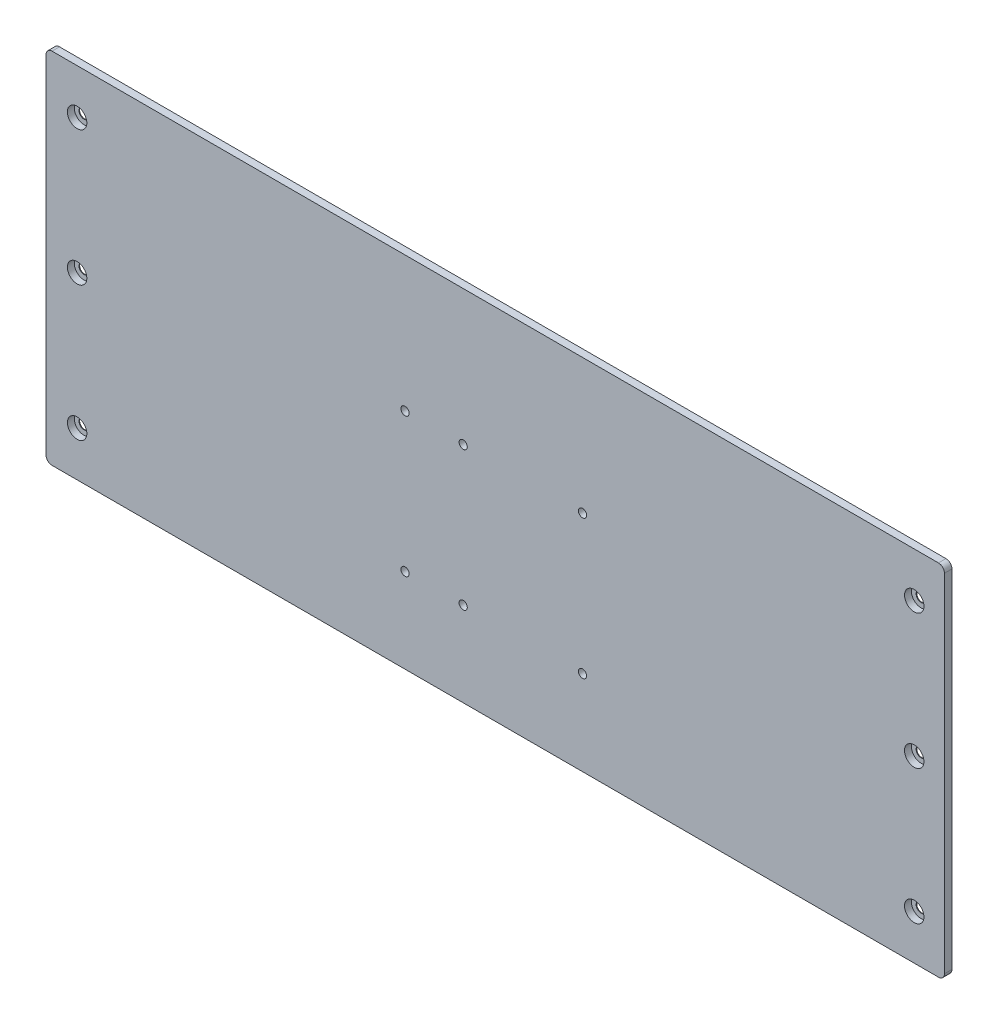
SolidWorks part; units mm, degrees
ref_plane "Front Plane" through (0, 0, 0) normal (0, 0, 1) x (1, 0, 0)
ref_plane "Top Plane" through (0, 0, 0) normal (0, 1, 0) x (1, 0, 0)
ref_plane "Right Plane" through (0, 0, 0) normal (1, 0, 0) x (0, 0, -1)
sketch "Sketch1" plane through (0, 0, 0) normal (0, 0, 1) x (1, 0, 0)
  line L1 (-296.5, -120) -> (296.5, -120)
  line L2 (-300.5, -116) -> (-300.5, 116)
  line L3 (-296.5, 120) -> (296.5, 120)
  line L4 (300.5, -116) -> (300.5, 116)
  line L5 (-300.5, -120) -> (300.5, 120) construction
  line L6 (-300.5, 120) -> (300.5, -120) construction
  arc A0 (-296.5, -120) -> (-300.5, -116) centre (-296.5, -116) cw
  arc A1 (296.5, -120) -> (300.5, -116) centre (296.5, -116) ccw
  arc A2 (300.5, 116) -> (296.5, 120) centre (296.5, 116) ccw
  arc A3 (-300.5, 116) -> (-296.5, 120) centre (-296.5, 116) cw
  point P0 (0, 0)
  dimension "D3" = 4
  dimension "D1" = 240
  dimension "D2" = 601
extrude "Boss-Extrude1" add sketch "Sketch1" along normal blind 5
hole_wizard "CBORE for M6 Pan Head Machine Screw1" positions "Sketch3" profile "Sketch2" counterbore size "M6" standard "ANSI Metric"
sketch "Sketch3" plane through (0, 0, 5) normal (0, 0, 1) x (1, 0, 0)
  line L0 (296.5, 120) -> (-296.5, 120) construction
  line L1 (-296.5, -120) -> (296.5, -120) construction
  point P2 (280.2732, 0)
  point P7 (280.2732, 90)
  point P9 (280.2732, -90)
  dimension "D1" = 30
  dimension "D2" = 30
sketch "Sketch2" plane through (280.2732, 0, 5) normal (1, 0, 0) x (0, -1, 0)
  line L0 (0, 0) -> (0, 6.9828)
  line L1 (0, 6.9828) -> (3.3, 5)
  line L2 (3.3, 5) -> (3.3, 4.625)
  line L3 (3.3, 4.625) -> (3.325, 4.6)
  line L4 (3.325, 4.6) -> (6.5, 4.6)
  line L5 (6.5, 4.6) -> (6.5, 0)
  line L6 (6.5, 0) -> (0, 0)
  line L9 (-3.3, 4.625) -> (-3.325, 4.6) construction
  line L10 (0, 6.9828) -> (-3.3, 5) construction
  line L11 (0, -6.35) -> (0, 107.95) construction
  dimension "Hole Dia." = 6.6
  dimension "Hole Depth" = 5
  dimension "C'Bore Dia." = 13
  dimension "C'Bore Depth" = 4.6
  dimension "Mid C'Sink Dia." = 6.65
  dimension "Mid C'Sink Angle" = 90
  dimension "Drill Angle" = 118
pattern_linear "LPattern1" count 2 spacing 560 along (-1, 0, 0) of "CBORE for M6 Pan Head Machine Screw1"
hole_wizard "M5 Clearance Hole1" positions "Sketch6" profile "Sketch4" hole size "M5" standard "ANSI Metric"
sketch "Sketch6" plane through (0, 0, 5) normal (0, 0, 1) x (1, 0, 0)
  point P0 (-60.375, -63.4197)
  point P2 (-21.468, -63.4197)
  point P4 (58.3682, -63.175)
sketch "Sketch4" plane through (-60.375, -63.4197, 5) normal (1, 0, 0) x (0, -1, 0)
  line L0 (0, 0) -> (0, 6.6524)
  line L1 (0, 6.6524) -> (2.75, 5)
  line L2 (2.75, 5) -> (2.75, 0)
  line L5 (2.75, 0) -> (0, 0)
  line L10 (0, 6.6524) -> (-2.75, 5) construction
  line L11 (0, -6.35) -> (0, 107.95) construction
  dimension "Hole Dia." = 5.5
  dimension "Hole Depth" = 5
  dimension "Drill Angle" = 118
pattern_linear "LPattern2" count 2 spacing 93 along (0, 1, 0) of "M5 Clearance Hole1"
